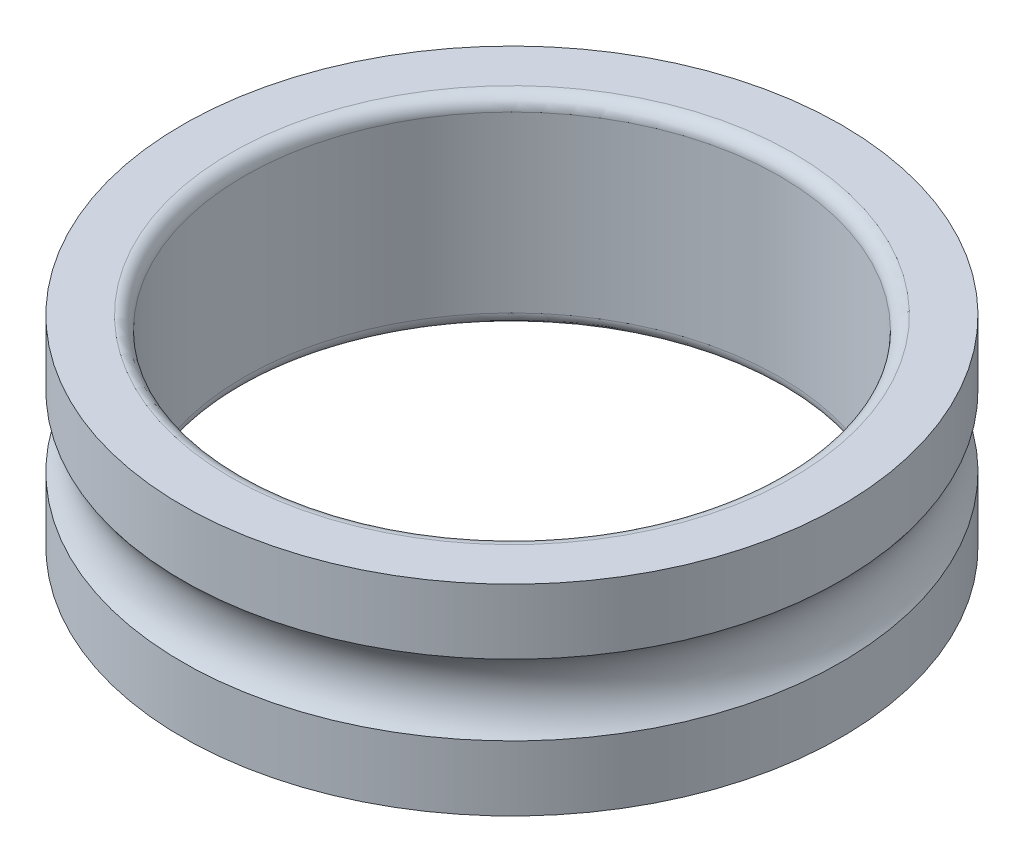
SolidWorks part; units mm, degrees
ref_plane "Front Plane" through (0, 0, 0) normal (0, 0, 1) x (1, 0, 0)
ref_plane "Top Plane" through (0, 0, 0) normal (0, 1, 0) x (1, 0, 0)
ref_plane "Right Plane" through (0, 0, 0) normal (1, 0, 0) x (0, 0, -1)
sketch "Sketch1" plane through (0, 0, 0) normal (0, 0, 1) x (1, 0, 0)
  line L0 (0, 0) -> (0, 46.1124) construction
  line L1 (-30.55, 7.5) -> (-24.625, 7.5) construction
  line L2 (-30.55, 0) -> (-34, 0)
  line L3 (-30.55, 0) -> (-30.55, 15)
  line L4 (-30.55, 15) -> (-34, 15)
  line L5 (-34, 0) -> (-34, 15)
  line L6 (-24.625, 0) -> (-20, 0)
  line L7 (-24.625, 0) -> (-24.625, 15)
  line L8 (-24.625, 15) -> (-20, 15)
  line L9 (-20, 0) -> (-20, 15)
  circle A0 centre (-27.5875, 7.5) radius 3.9688
  dimension "D6" = 7.9375
  dimension "D1" = 15
  dimension "D2" = 34
  dimension "D3" = 30.55
  dimension "D4" = 20
  dimension "D5" = 24.625
revolve "Revolve2" add sketch "Sketch1" angle 360 about L0
fillet "Fillet1" radius 1 2 edges at (0, 0, -20) (0, 15, -20)
